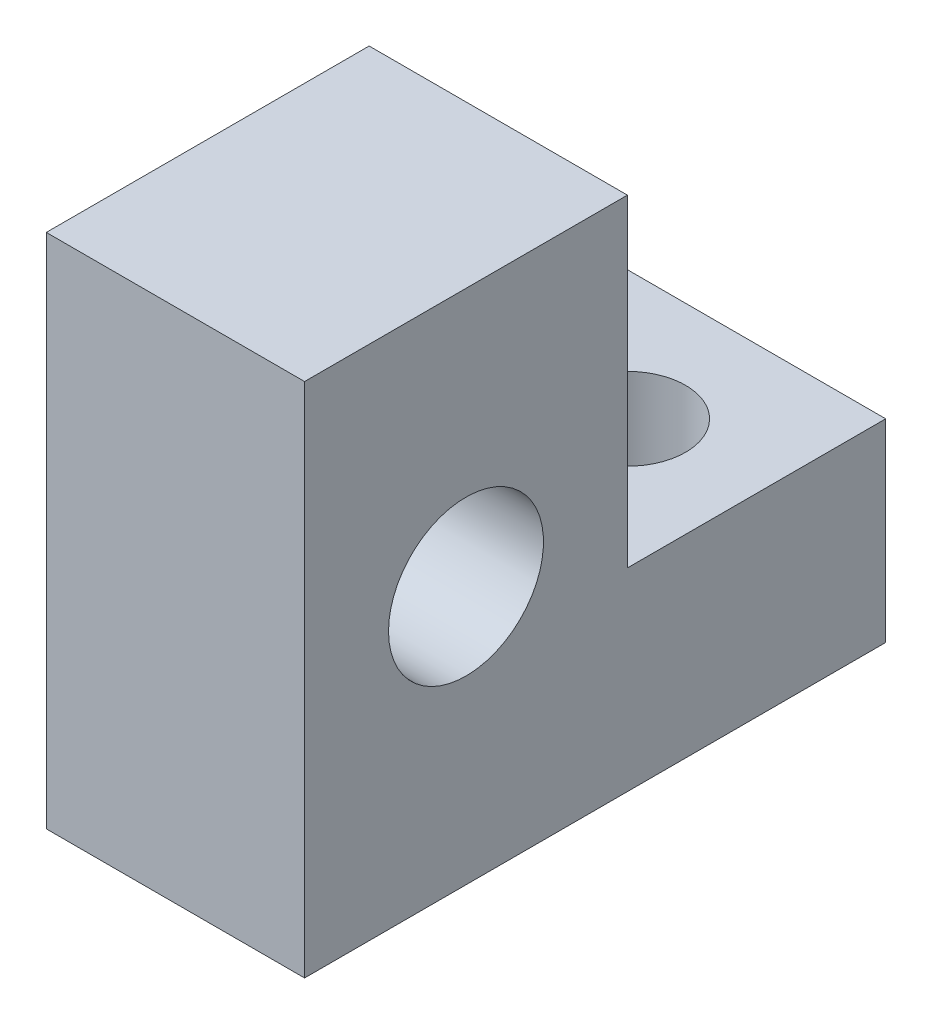
SolidWorks part; units mm, degrees
ref_plane "Front Plane" through (0, 0, 0) normal (0, 0, 1) x (1, 0, 0)
ref_plane "Top Plane" through (0, 0, 0) normal (0, 1, 0) x (1, 0, 0)
ref_plane "Right Plane" through (0, 0, 0) normal (1, 0, 0) x (0, 0, -1)
sketch "Sketch1" plane through (0, 0, 0) normal (0, 1, 0) x (1, 0, 0)
  line L1 (-2, -2.5) -> (2, -2.5)
  line L2 (-2, -2.5) -> (-2, 2.5)
  line L3 (-2, 2.5) -> (2, 2.5)
  line L4 (2, -2.5) -> (2, 2.5)
  line L5 (-2, -2.5) -> (2, 2.5) construction
  line L6 (-2, 2.5) -> (2, -2.5) construction
  point P0 (0, 0)
  dimension "D1" = 4
  dimension "D2" = 5
extrude "Boss-Extrude1" add sketch "Sketch1" along normal mid plane 8
sketch "Sketch2" plane through (0, 0, -2.5) normal (0, 0, -1) x (-1, 0, 0)
  line L0 (2, 4) -> (2, -4) construction
  line L1 (-2, -4) -> (2, -4)
  line L2 (-2, -4) -> (-2, -1)
  line L3 (-2, -1) -> (2, -1)
  line L4 (2, -4) -> (2, -1)
  dimension "D1" = 3
extrude "Boss-Extrude2" add sketch "Sketch2" along normal blind 4
sketch "Sketch3" plane through (-2, 0, 0) normal (-1, 0, 0) x (0, 0, 1)
  line L0 (-2.5, 4) -> (2.5, 4) construction
  line L6 (-1.625, 2.125) -> (1.625, 2.125)
  line L7 (-1.625, 2.125) -> (-1.625, -2.125)
  line L8 (-1.625, -2.125) -> (1.625, -2.125)
  line L9 (1.625, 2.125) -> (1.625, -2.125)
  line L10 (-1.625, 2.125) -> (1.625, -2.125) construction
  line L11 (-1.625, -2.125) -> (1.625, 2.125) construction
  point P0 (0, 0)
  dimension "D1" = 3.25
  dimension "D2" = 4.25
  dimension "D3" = 4
sketch "Sketch4" plane through (0, -1, 0) normal (0, 1, 0) x (1, 0, 0)
  line L0 (-2, 6.5) -> (-2, 2.5) construction
  point P0 (0, 4.5)
  point P5 (-2, 4.5)
hole_wizard "M1.6 Clearance Hole1" positions "Sketch5" profile "Sketch6" hole size "M1.6" standard "ISO"
sketch "Sketch5" plane through (0, -1, 0) normal (0, 1, 0) x (1, 0, 0)
  point P0 (0, 4.5)
sketch "Sketch6" plane through (0, -1, -4.5) normal (1, 0, 0) x (0, 0, 1)
  line L0 (0, 0) -> (0, 4.5408)
  line L1 (0, 4.5408) -> (0.9, 4)
  line L2 (0.9, 4) -> (0.9, 0)
  line L5 (0.9, 0) -> (0, 0)
  line L10 (0, 4.5408) -> (-0.9, 4) construction
  line L11 (0, -6.35) -> (0, 107.95) construction
  dimension "Hole Dia." = 1.8
  dimension "Hole Depth" = 4
  dimension "Drill Angle" = 118
extrude "Cut-Extrude1" [suppressed] cut sketch "Sketch3" against normal up to surface (4 mm away)
sketch "Sketch7" plane through (-2, 0, 0) normal (-1, 0, 0) x (0, 0, 1)
  line L0 (-2.5, 4) -> (2.5, 4) construction
  point P0 (0, 0)
  dimension "D1" = 4
hole_wizard "M2 Clearance Hole1" positions "Sketch8" profile "Sketch9" hole size "M2" standard "ISO"
sketch "Sketch8" plane through (-2, 0, 0) normal (-1, 0, 0) x (0, 0, 1)
  point P0 (0, 0)
sketch "Sketch9" plane through (-2, 0, 0) normal (0, 1, 0) x (0, 0, 1)
  line L0 (0, 0) -> (0, 4.721)
  line L1 (0, 4.721) -> (1.2, 4)
  line L2 (1.2, 4) -> (1.2, 0)
  line L5 (1.2, 0) -> (0, 0)
  line L10 (0, 4.721) -> (-1.2, 4) construction
  line L11 (0, -6.35) -> (0, 107.95) construction
  dimension "Hole Dia." = 2.4
  dimension "Hole Depth" = 4
  dimension "Drill Angle" = 118
